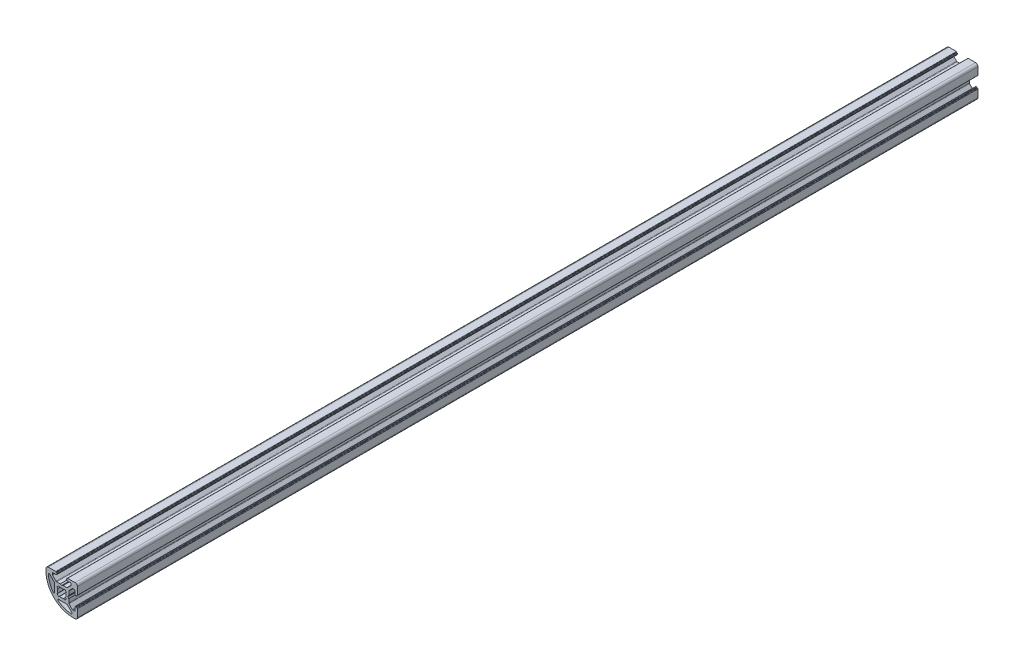
SolidWorks part; units mm, degrees
ref_plane "Front Plane" through (0, 0, 0) normal (0, 0, 1) x (1, 0, 0)
ref_plane "Top Plane" through (0, 0, 0) normal (0, 1, 0) x (1, 0, 0)
ref_plane "Right Plane" through (0, 0, 0) normal (1, 0, 0) x (0, 0, -1)
sketch "Sketch1" plane through (0, 0, 0) normal (0, 0, 1) x (1, 0, 0)
  line L0 (1.2582, 2.4453) -> (1.8871, 2.9477)
  line L1 (1.2582, -2.4453) -> (1.8871, -2.9477)
  line L2 (3.2322, 4.5654) -> (0.9536, 4.5654)
  line L3 (3.2322, -4.5) -> (-2, -4.5)
  line L4 (-1.2582, -2.4453) -> (-1.8871, -2.9477)
  line L5 (-4.6464, 3.5858) -> (-7.6257, 6.565)
  line L6 (-10, 7) -> (-10, 8.5)
  line L7 (-2.4453, -1.2582) -> (-2.9477, -1.8871)
  line L8 (-2.4453, 1.2582) -> (-2.9477, 1.8871)
  line L9 (-4.5, 3.2322) -> (-4.5, -2)
  line L10 (-1.2582, 2.4453) -> (-1.8871, 2.9477)
  line L11 (-3.2322, 4.5654) -> (-0.9536, 4.5654)
  line L12 (-3.2, 9.45) -> (-3.35, 9.45)
  line L13 (-3, 8.9321) -> (-3, 9.25)
  line L14 (-3.4918, 8.4403) -> (-5.5082, 8.4403)
  line L15 (-3.5763, 4.7027) -> (-5.8441, 6.8535)
  line L16 (-6, 7.2162) -> (-6, 7.9485)
  line L17 (-0.8536, 4.5387) -> (-0.1, 4.1036)
  line L18 (0.8536, 4.5387) -> (0.1, 4.1036)
  line L19 (-3.75, 10) -> (-8.5, 10)
  line L20 (-3.55, 9.65) -> (-3.55, 9.8)
  line L21 (4.5, -3.2322) -> (4.5, -0.9536)
  line L22 (9.65, -3.55) -> (9.8, -3.55)
  line L23 (7, -10) -> (8.5, -10)
  line L24 (4.6372, -3.5763) -> (6.788, -5.8441)
  line L25 (3.5858, -4.6464) -> (6.565, -7.6257)
  line L26 (8.3748, -3.4918) -> (8.3748, -5.5082)
  line L27 (9.45, -3.2) -> (9.45, -3.35)
  line L28 (8.8666, -3) -> (9.25, -3)
  line L29 (7.1508, -6) -> (7.883, -6)
  line L30 (10, -3.75) -> (10, -8.5)
  line L31 (9.65, 3.55) -> (9.8, 3.55)
  line L32 (8.3748, 3.4918) -> (8.3748, 5.5082)
  line L33 (4.6372, 3.5763) -> (6.788, 5.8441)
  line L34 (2.4453, 1.2582) -> (2.9477, 1.8871)
  line L35 (2.4453, -1.2582) -> (2.9477, -1.8871)
  line L36 (4.5, 3.2322) -> (4.5, 0.9536)
  line L37 (4.4732, 0.8536) -> (4.0381, 0.1)
  line L38 (4.4732, -0.8536) -> (4.0381, -0.1)
  line L39 (9.45, 3.2) -> (9.45, 3.35)
  line L40 (8.8666, 3) -> (9.25, 3)
  line L42 (3.5763, 4.7027) -> (5.8441, 6.8535)
  line L43 (3.4918, 8.4403) -> (5.5082, 8.4403)
  line L44 (3.2, 9.45) -> (3.35, 9.45)
  line L45 (3, 8.9321) -> (3, 9.25)
  line L46 (6, 7.2162) -> (6, 7.9485)
  line L47 (7.1508, 6) -> (7.883, 6)
  line L48 (10, 3.75) -> (10, 8.5)
  line L49 (3.75, 10) -> (8.5, 10)
  line L50 (3.55, 9.65) -> (3.55, 9.8)
  line L51 (0, 13.6082) -> (0, -13.4183) construction
  line L52 (-13.988, 0) -> (15.7602, 0) construction
  arc A0 (-2.3, -5.4) -> (6.1852, -8.4786) centre (7, 7) ccw
  arc A1 (-10, 7) -> (7, -10) centre (7, 7) ccw
  arc A2 (-3.55, 9.65) -> (-3.35, 9.45) centre (-3.35, 9.65) ccw
  arc A3 (-8.5, 10) -> (-10, 8.5) centre (-8.5, 8.5) ccw
  arc A4 (-5.4, -2.3) -> (-4.5, -2) centre (-5, -2) ccw
  arc A5 (-8.4786, 6.1852) -> (-5.4, -2.3) centre (7, 7) ccw
  arc A6 (-2.9477, -1.8871) -> (-1.8871, -2.9477) centre (0, 0) ccw
  arc A7 (-2, -4.5) -> (-2.3, -5.4) centre (-2, -5) ccw
  arc A8 (-1.2582, -2.4453) -> (1.2582, -2.4453) centre (0, 0) ccw
  arc A9 (-7.6257, 6.565) -> (-8.4786, 6.1852) centre (-7.9793, 6.2115) ccw
  arc A10 (-1.8871, 2.9477) -> (-2.9477, 1.8871) centre (0, 0) ccw
  arc A11 (-4.5, 3.2322) -> (-4.6464, 3.5858) centre (-5, 3.2322) ccw
  arc A12 (1.2582, 2.4453) -> (-1.2582, 2.4453) centre (0, 0) ccw
  arc A13 (-2.4453, 1.2582) -> (-2.4453, -1.2582) centre (0, 0) ccw
  arc A14 (-3, 9.25) -> (-3.2, 9.45) centre (-3.2, 9.25) ccw
  arc A15 (-3.4918, 8.4403) -> (-3, 8.9321) centre (-3.4918, 8.9321) ccw
  arc A16 (-3.5763, 4.7027) -> (-3.2322, 4.5654) centre (-3.2322, 5.0654) ccw
  arc A17 (-6, 7.2162) -> (-5.8441, 6.8535) centre (-5.5, 7.2162) ccw
  arc A18 (-5.5082, 8.4403) -> (-6, 7.9485) centre (-5.5082, 7.9485) ccw
  arc A19 (-0.1, 4.1036) -> (0.1, 4.1036) centre (0, 4.2768) ccw
  arc A20 (0.9536, 4.5654) -> (0.8536, 4.5387) centre (0.9536, 4.3654) ccw
  arc A21 (-0.8536, 4.5387) -> (-0.9536, 4.5654) centre (-0.9536, 4.3654) ccw
  arc A22 (-3.55, 9.8) -> (-3.75, 10) centre (-3.75, 9.8) ccw
  arc A23 (3.35, 9.45) -> (3.55, 9.65) centre (3.35, 9.65) ccw
  arc A24 (10, 8.5) -> (8.5, 10) centre (8.5, 8.5) ccw
  arc A25 (1.8871, -2.9477) -> (2.9477, -1.8871) centre (0, 0) ccw
  arc A26 (8.5, -10) -> (10, -8.5) centre (8.5, -8.5) ccw
  arc A27 (6.1852, -8.4786) -> (6.565, -7.6257) centre (6.2115, -7.9793) ccw
  arc A28 (4.5, -3.2322) -> (4.6372, -3.5763) centre (5, -3.2322) ccw
  arc A29 (3.5858, -4.6464) -> (3.2322, -4.5) centre (3.2322, -5) ccw
  arc A30 (9.45, -3.2) -> (9.25, -3) centre (9.25, -3.2) ccw
  arc A31 (9.45, -3.35) -> (9.65, -3.55) centre (9.65, -3.35) ccw
  arc A32 (8.8666, -3) -> (8.3748, -3.4918) centre (8.8666, -3.4918) ccw
  arc A33 (6.788, -5.8441) -> (7.1508, -6) centre (7.1508, -5.5) ccw
  arc A34 (7.883, -6) -> (8.3748, -5.5082) centre (7.883, -5.5082) ccw
  arc A35 (10, -3.75) -> (9.8, -3.55) centre (9.8, -3.75) ccw
  arc A36 (2.4453, -1.2582) -> (2.4453, 1.2582) centre (0, 0) ccw
  arc A37 (2.9477, 1.8871) -> (1.8871, 2.9477) centre (0, 0) ccw
  arc A38 (4.0381, 0.1) -> (4.0381, -0.1) centre (4.2113, 0) ccw
  arc A39 (4.5, -0.9536) -> (4.4732, -0.8536) centre (4.3, -0.9536) ccw
  arc A40 (4.4732, 0.8536) -> (4.5, 0.9536) centre (4.3, 0.9536) ccw
  arc A41 (4.6372, 3.5763) -> (4.5, 3.2322) centre (5, 3.2322) ccw
  arc A42 (9.65, 3.55) -> (9.45, 3.35) centre (9.65, 3.35) ccw
  arc A43 (9.25, 3) -> (9.45, 3.2) centre (9.25, 3.2) ccw
  arc A44 (8.3748, 3.4918) -> (8.8666, 3) centre (8.8666, 3.4918) ccw
  arc A45 (6, 7.9485) -> (5.5082, 8.4403) centre (5.5082, 7.9485) ccw
  arc A46 (3.2, 9.45) -> (3, 9.25) centre (3.2, 9.25) ccw
  arc A47 (3, 8.9321) -> (3.4918, 8.4403) centre (3.4918, 8.9321) ccw
  arc A48 (3.2322, 4.5654) -> (3.5763, 4.7027) centre (3.2322, 5.0654) ccw
  arc A49 (5.8441, 6.8535) -> (6, 7.2162) centre (5.5, 7.2162) ccw
  arc A50 (7.1508, 6) -> (6.788, 5.8441) centre (7.1508, 5.5) ccw
  arc A51 (8.3748, 5.5082) -> (7.883, 6) centre (7.883, 5.5082) ccw
  arc A52 (9.8, 3.55) -> (10, 3.75) centre (9.8, 3.75) ccw
  arc A53 (3.75, 10) -> (3.55, 9.8) centre (3.75, 9.8) ccw
  dimension "D1" = 5.5
  dimension "D5" = 17
  dimension "D7" = 5.5
  dimension "D8" = 12
  dimension "D2" = 20
  dimension "D3" = 20
  dimension "D4" = 10
  dimension "D6" = 6
  dimension "D9" = 12
extrude "Extrude1" add sketch "Sketch1" along normal blind 574
